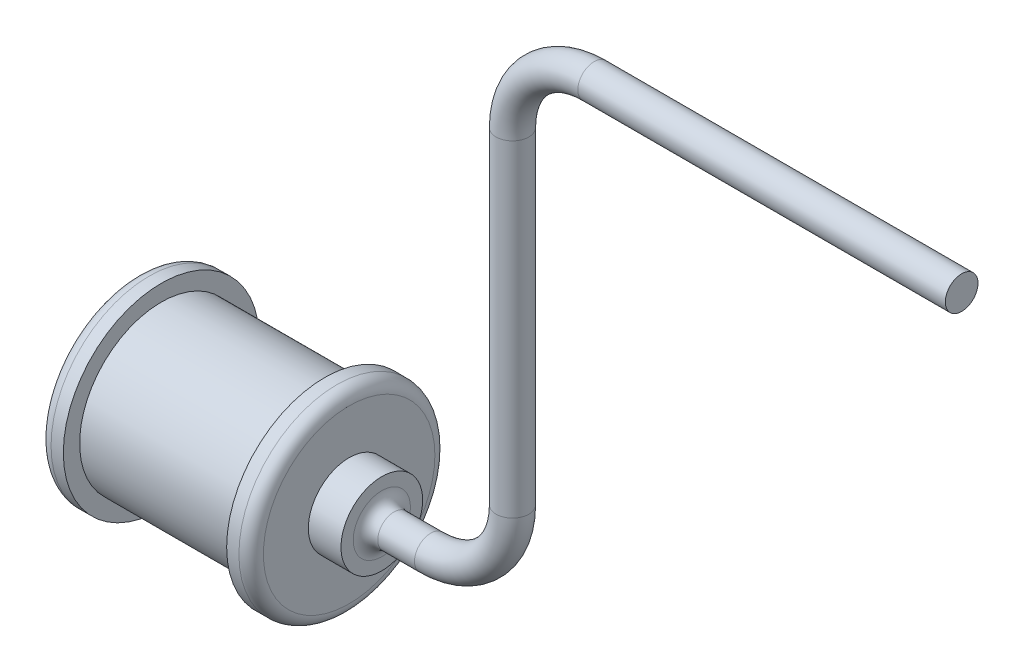
SolidWorks part; units mm, degrees
ref_plane "Front Plane" through (0, 0, 0) normal (0, 0, 1) x (1, 0, 0)
ref_plane "Top Plane" through (0, 0, 0) normal (0, 1, 0) x (1, 0, 0)
ref_plane "Right Plane" through (0, 0, 0) normal (1, 0, 0) x (0, 0, -1)
sketch "Sketch2" plane through (0, 0, 0) normal (1, 0, 0) x (0, 0, -1)
  circle A0 centre (0, 0) radius 15.24
  dimension "D1" = 30.48
extrude "Boss-Extrude1" add sketch "Sketch2" along normal blind 3.81
sketch "Sketch3" plane through (3.81, 0, 0) normal (1, 0, 0) x (0, 0, -1)
  circle A0 centre (0, 0) radius 12.7
  dimension "D1" = 25.4
extrude "Boss-Extrude2" add sketch "Sketch3" along normal blind 25.4
sketch "Sketch4" plane through (29.21, 0, 0) normal (1, 0, 0) x (0, 0, -1)
  circle A0 centre (0, 0) radius 15.24
  dimension "D1" = 30.48
extrude "Boss-Extrude3" add sketch "Sketch4" along normal blind 3.81
sketch "Sketch5" plane through (0, 0, 0) normal (0, 0, 1) x (1, 0, 0)
  line L0 (33.02, -15.24) -> (33.02, 15.24) construction
  line L1 (33.02, -15.24) -> (33.02, 15.24)
  line L2 (33.02, 0) -> (45.72, 0)
  line L3 (58.42, 12.7) -> (58.42, 63.5)
  line L4 (71.12, 76.2) -> (128.27, 76.2)
  arc A0 (45.72, 0) -> (58.42, 12.7) centre (45.72, 12.7) ccw
  arc A1 (58.42, 63.5) -> (71.12, 76.2) centre (71.12, 63.5) cw
  point P9 (58.42, 0)
  point P12 (58.42, 76.2)
  dimension "D4" = 12.7
  dimension "D5" = 12.7
  dimension "D1" = 25.4
  dimension "D2" = 76.2
  dimension "D3" = 69.85
sketch "Sketch6" plane through (33.02, 0, 0) normal (1, 0, 0) x (0, 0, -1)
  circle A0 centre (0, 0) radius 2.54
  dimension "D1" = 5.08
sweep "Sweep1" add profiles "Sketch6" path "Sketch5"
fillet "Fillet1" radius 1.905 2 edges at (0, 0, -15.24) (33.02, 0, -15.24)
sketch "Sketch7" plane through (0, 0, 0) normal (-1, 0, 0) x (0, 0, 1)
  circle A0 centre (0, 0) radius 6.35
  dimension "D1" = 12.7
extrude "Boss-Extrude4" add sketch "Sketch7" along normal blind 5.08
sketch "Sketch8" plane through (33.02, 0, 0) normal (1, 0, 0) x (0, 0, -1)
  circle A0 centre (0, 0) radius 6.35
  dimension "D1" = 12.7
extrude "Boss-Extrude5" add sketch "Sketch8" along normal blind 5.08
fillet "Fillet2" radius 1.905 1 edges at (38.1, 0, -2.54)
